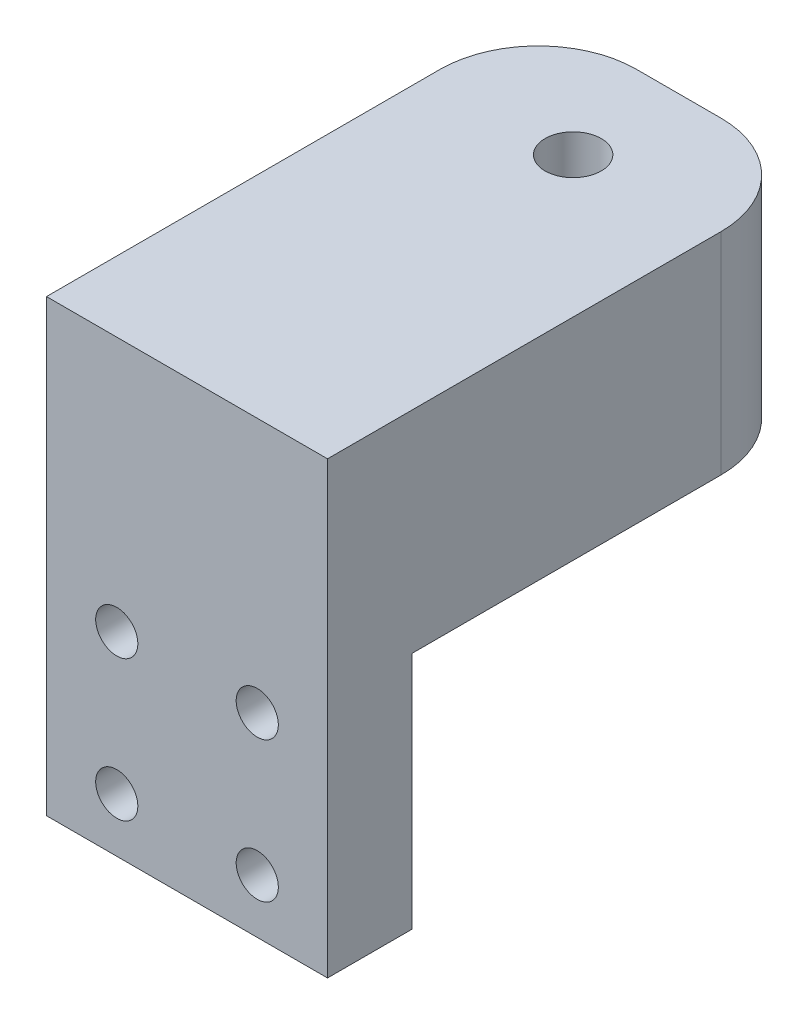
SolidWorks part; units mm, degrees
ref_plane "Спереди" through (0, 0, 0) normal (0, 0, 1) x (1, 0, 0)
ref_plane "Сверху" through (0, 0, 0) normal (0, 1, 0) x (1, 0, 0)
ref_plane "Справа" through (0, 0, 0) normal (1, 0, 0) x (0, 0, -1)
sketch "Эскиз1" plane through (0, 0, 0) normal (0, 0, 1) x (1, 0, 0)
  line L1 (-10, -10) -> (10, -10)
  line L2 (-10, -10) -> (-10, 10)
  line L3 (-10, 10) -> (10, 10)
  line L4 (10, -10) -> (10, 10)
  line L5 (-10, -10) -> (10, 10) construction
  line L6 (-10, 10) -> (10, -10) construction
  line L7 (-5, -6.152) -> (5, -6.152)
  line L8 (-5, -6.152) -> (-5, 3.848)
  line L9 (-5, 3.848) -> (5, 3.848)
  line L10 (5, -6.152) -> (5, 3.848)
  line L11 (-5, -6.152) -> (5, 3.848) construction
  line L12 (-5, 3.848) -> (5, -6.152) construction
  circle A0 centre (-5, -6.152) radius 1.5
  circle A1 centre (-5, 3.848) radius 1.5
  circle A2 centre (5, 3.848) radius 1.5
  circle A3 centre (5, -6.152) radius 1.5
  point P0 (0, 0)
  point P6 (0, -1.152)
  dimension "D5" = 3
  dimension "D6" = 3
  dimension "D7" = 3
  dimension "D8" = 3
  dimension "D1" = 20
  dimension "D2" = 20
  dimension "D3" = 10
  dimension "D4" = 10
extrude "Бобышка-Вытянуть1" add sketch "Эскиз1" along normal blind 6 contours L1 L4 L3 L2 A3 L7 A0 L8 A1 L9 A2 L10 | A3 L10 A2 L9 A1 L8 A0 L7
sketch "Эскиз2" plane through (0, 0, 0) normal (0, 0, -1) x (-1, 0, 0)
  line L0 (10, -10) -> (10, 10) construction
  line L1 (-10, 10) -> (10, 10)
  line L2 (-10, 10) -> (-10, 7)
  line L3 (-10, 7) -> (10, 7)
  line L4 (10, 10) -> (10, 7)
  dimension "D1" = 3
extrude "Бобышка-Вытянуть2" add sketch "Эскиз2" along normal blind 29
sketch "Эскиз3" plane through (0, 10, 0) normal (0, 1, 0) x (1, 0, 0)
  line L1 (-10, 29) -> (10, 29)
  line L2 (-10, 29) -> (-10, -6)
  line L3 (-10, -6) -> (10, -6)
  line L4 (10, 29) -> (10, -6)
extrude "Бобышка-Вытянуть3" add sketch "Эскиз3" along normal blind 12
sketch "Эскиз4" plane through (0, 22, 0) normal (0, 1, 0) x (1, 0, 0)
  line L0 (-10, 8) -> (10, 8)
  line L1 (-3, 29) -> (3, 29)
  line L2 (-10, 22) -> (-10, -6)
  line L3 (-10, -6) -> (10, -6)
  line L4 (10, 22) -> (10, -6)
  line L5 (0, 29) -> (0, -6)
  line L7 (-10, 29) -> (10, 29)
  line L8 (-10, 29) -> (-10, -6)
  line L9 (-10, -6) -> (10, -6)
  line L10 (10, 29) -> (10, -6)
  arc A0 (10, 22) -> (3, 29) centre (3, 22) ccw
  arc A1 (-10, 22) -> (-3, 29) centre (-3, 22) cw
  circle A2 centre (0, 21.4823) radius 2
  point P12 (-10, 29)
  point P17 (0, 22)
  point P18 (0, 0)
  point P20 (0, 21.4823)
  line M8 (-10, 29) -> (-10, -6)
  line M10 (10, -6) -> (10, 29)
  line M11 (10, 29) -> (-10, 29)
  dimension "D1" = 7
  dimension "D2" = 4
extrude "Вырез-Вытянуть1" cut sketch "Эскиз4" against normal through all contours A1 M8 M11 | L5 A2 | L5 A2 | A0 M10 M11
